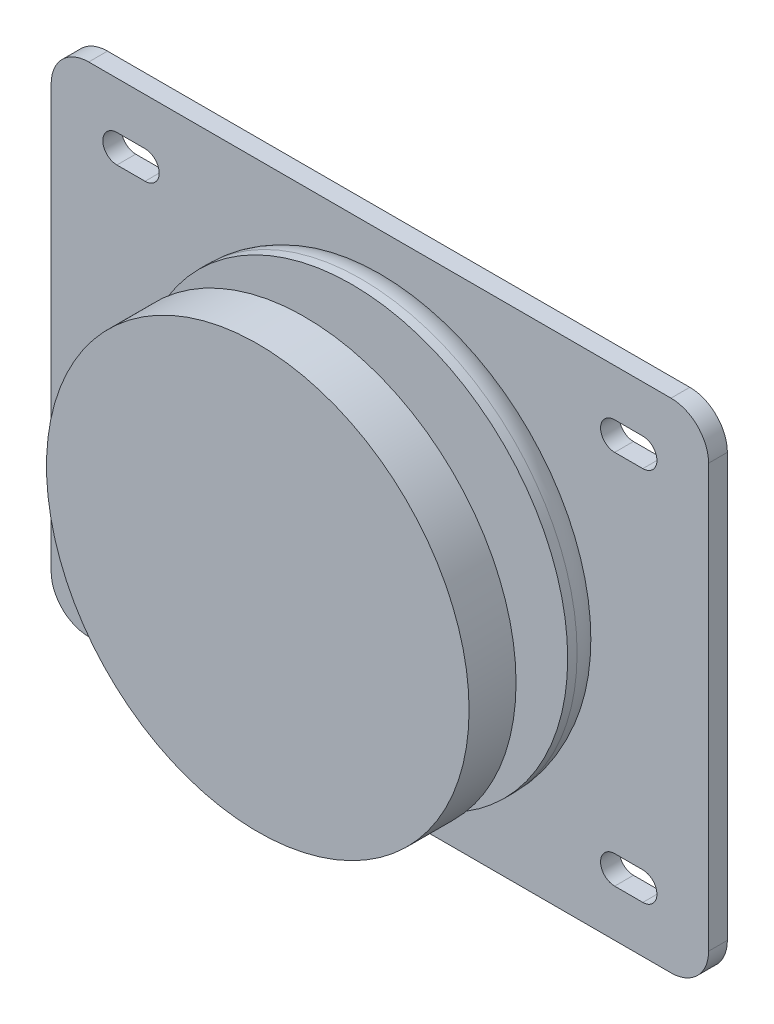
SolidWorks part; units mm, degrees
ref_plane "前视基准面" through (0, 0, 0) normal (0, 0, 1) x (1, 0, 0)
ref_plane "上视基准面" through (0, 0, 0) normal (0, 1, 0) x (1, 0, 0)
ref_plane "右视基准面" through (0, 0, 0) normal (1, 0, 0) x (0, 0, -1)
sketch "草图1" plane through (0, 0, 0) normal (0, 0, 1) x (1, 0, 0)
  circle A0 centre (0, 0) radius 23
  dimension "D1" = 46
extrude "凸台-拉伸1" add sketch "草图1" along normal blind 5
fillet "圆角1" radius 4 1 edges at (23, 0, 0)
sketch "草图4" plane through (0, 0, 0) normal (0, 0, 1) x (1, 0, 0)
  line L1 (-31, -26.5) -> (31, -26.5)
  line L2 (-35, -22.5) -> (-35, 22.5)
  line L3 (-31, 26.5) -> (31, 26.5)
  line L4 (35, -22.5) -> (35, 22.5)
  line L5 (-35, -26.5) -> (35, 26.5) construction
  line L6 (-35, 26.5) -> (35, -26.5) construction
  arc A0 (31, 26.5) -> (35, 22.5) centre (31, 22.5) cw
  arc A1 (-35, 22.5) -> (-31, 26.5) centre (-31, 22.5) cw
  arc A2 (-31, -26.5) -> (-35, -22.5) centre (-31, -22.5) cw
  arc A3 (31, -26.5) -> (35, -22.5) centre (31, -22.5) ccw
  point P0 (0, 0)
  dimension "D3" = 4
  dimension "D4" = 4
  dimension "D5" = 4
  dimension "D6" = 4
  dimension "D1" = 53
  dimension "D2" = 70
extrude "凸台-拉伸2" add sketch "草图4" along normal blind 2
sketch "草图5" [suppressed] plane through (0, 0, 0) normal (0, 0, -1) x (-1, 0, 0)
  line L0 (27.4854, 24.5657) -> (30.4854, 24.5657)
  line L1 (30.4854, 21.5657) -> (27.4854, 21.5657)
  line L2 (0, 0) -> (35, 0) construction
  line L3 (35, 22.5) -> (35, -22.5) construction
  line L4 (35, 0) -> (-36.8686, 0) construction
  line L5 (0, -28.1375) -> (0, 28.5777) construction
  line L6 (30.4854, -21.5657) -> (27.4854, -21.5657)
  line L7 (27.4854, -24.5657) -> (30.4854, -24.5657)
  line L8 (-27.4854, 24.5657) -> (-30.4854, 24.5657)
  line L9 (-30.4854, 21.5657) -> (-27.4854, 21.5657)
  line L10 (-27.4854, -24.5657) -> (-30.4854, -24.5657)
  line L11 (-30.4854, -21.5657) -> (-27.4854, -21.5657)
  arc A0 (30.4854, 21.5657) -> (30.4854, 24.5657) centre (30.4854, 23.0657) ccw
  arc A1 (27.4854, 24.5657) -> (27.4854, 21.5657) centre (27.4854, 23.0657) ccw
  arc A2 (27.4854, -24.5657) -> (27.4854, -21.5657) centre (27.4854, -23.0657) cw
  arc A3 (30.4854, -21.5657) -> (30.4854, -24.5657) centre (30.4854, -23.0657) cw
  arc A4 (-30.4854, 21.5657) -> (-30.4854, 24.5657) centre (-30.4854, 23.0657) cw
  arc A5 (-27.4854, 24.5657) -> (-27.4854, 21.5657) centre (-27.4854, 23.0657) cw
  arc A6 (-30.4854, -21.5657) -> (-30.4854, -24.5657) centre (-30.4854, -23.0657) ccw
  arc A7 (-27.4854, -24.5657) -> (-27.4854, -21.5657) centre (-27.4854, -23.0657) ccw
  dimension "D1" = 3
  dimension "D2" = 3
  dimension "D3" = 3
extrude "切除-拉伸2" [suppressed] cut sketch "草图5" against normal through all
sketch "草图6" plane through (0, 0, 0) normal (0, 0, -1) x (-1, 0, 0)
  line L0 (0, 0) -> (0, 28.0368) construction
  line L1 (28, 21.5) -> (25, 21.5)
  line L2 (25, 18.5) -> (28, 18.5)
  line L3 (0, 28.0368) -> (0, -27.4489) construction
  line L4 (0, 0) -> (-35.6064, 0) construction
  line L5 (-35.6064, 0) -> (37.0762, 0) construction
  line L6 (-31, 26.5) -> (31, 26.5) construction
  line L7 (35, 22.5) -> (35, -22.5) construction
  line L8 (25, -18.5) -> (28, -18.5)
  line L9 (28, -21.5) -> (25, -21.5)
  line L10 (-28, -21.5) -> (-25, -21.5)
  line L11 (-25, -18.5) -> (-28, -18.5)
  line L12 (-28, 21.5) -> (-25, 21.5)
  line L13 (-25, 18.5) -> (-28, 18.5)
  arc A0 (25, 21.5) -> (25, 18.5) centre (25, 20) ccw
  arc A1 (28, 18.5) -> (28, 21.5) centre (28, 20) ccw
  arc A2 (28, -18.5) -> (28, -21.5) centre (28, -20) cw
  arc A3 (25, -21.5) -> (25, -18.5) centre (25, -20) cw
  arc A4 (-28, -18.5) -> (-28, -21.5) centre (-28, -20) ccw
  arc A5 (-25, -21.5) -> (-25, -18.5) centre (-25, -20) ccw
  arc A6 (-25, 21.5) -> (-25, 18.5) centre (-25, 20) cw
  arc A7 (-28, 18.5) -> (-28, 21.5) centre (-28, 20) cw
  dimension "D1" = 3
  dimension "D2" = 3
  dimension "D3" = 3
  dimension "D4" = 5
  dimension "D5" = 7
extrude "切除-拉伸3" cut sketch "草图6" against normal through all
sketch "草图7" plane through (0, 0, 5) normal (0, 0, 1) x (1, 0, 0)
  circle A0 centre (0, 0) radius 14
  dimension "D1" = 28
extrude "凸台-拉伸3" add sketch "草图7" along normal blind 5
sketch "草图8" plane through (0, 0, 10) normal (0, 0, 1) x (1, 0, 0)
  circle A0 centre (0, 0) radius 22.5
  dimension "D1" = 45
extrude "凸台-拉伸4" add sketch "草图8" along normal blind 5
